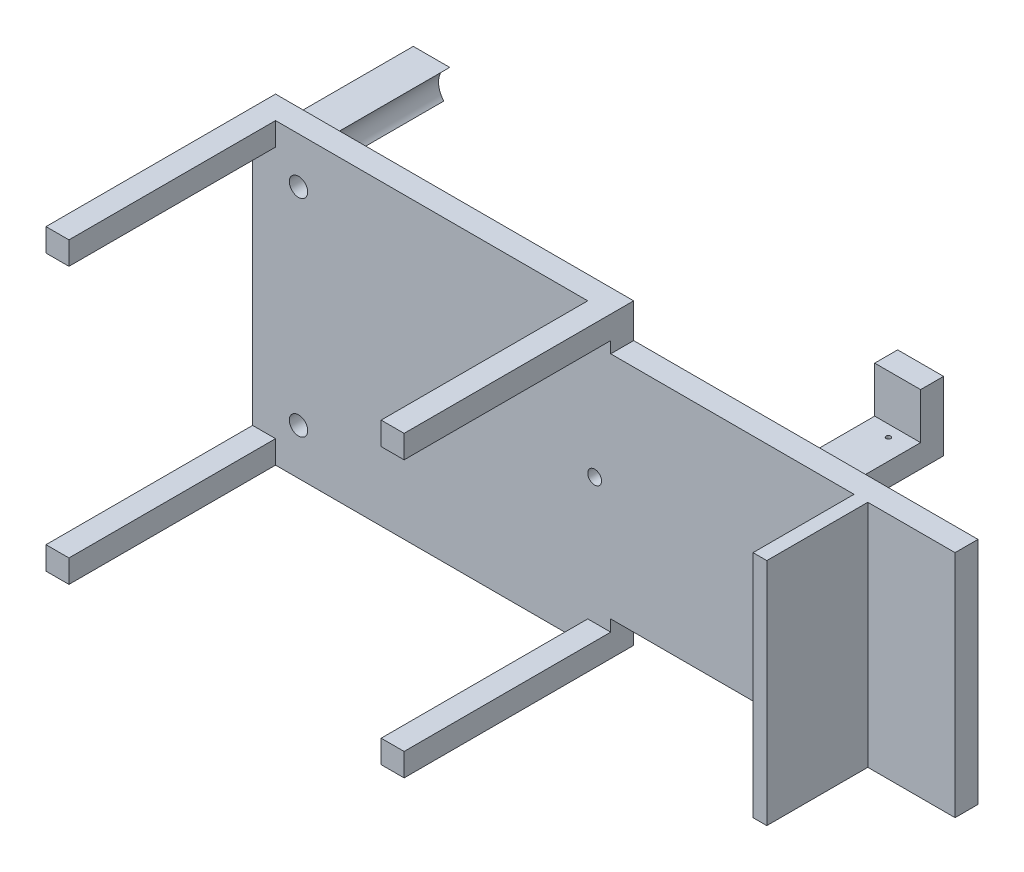
SolidWorks part; units mm, degrees
ref_plane "Alzado" through (0, 0, 0) normal (0, 0, 1) x (1, 0, 0)
ref_plane "Planta" through (0, 0, 0) normal (0, 1, 0) x (1, 0, 0)
ref_plane "Vista lateral" through (0, 0, 0) normal (1, 0, 0) x (0, 0, -1)
sketch "Croquis1" plane through (0, 0, 0) normal (0, 0, 1) x (1, 0, 0)
  line L1 (-76.5, -32.5) -> (1.5, -32.5)
  line L2 (-76.5, -32.5) -> (-76.5, 32.5)
  line L3 (-76.5, 32.5) -> (1.5, 32.5)
  line L4 (76.5, -25) -> (76.5, 25)
  line L5 (-76.5, 0) -> (127.0996, 0) construction
  line L6 (1.5, 32.5) -> (-3.5, 32.5)
  line L7 (-76.5, 27.5) -> (1.5, 27.5) construction
  line L8 (-76.5, -27.5) -> (1.5, -27.5) construction
  line L9 (-71.5, 0) -> (-61.5, 0) construction
  line L10 (1.5, -32.5) -> (1.5, 32.5)
  line L11 (-76.5, -32.5) -> (-71.5, -32.5)
  line L12 (1.5, -32.5) -> (-3.5, -32.5)
  line L13 (1.5, -32.5) -> (1.5, -27.5)
  line L14 (1.5, -27.5) -> (-3.5, -27.5)
  line L15 (76.5, 25) -> (1.5, 25)
  line L16 (76.5, -25) -> (1.5, -25)
  line L17 (-3.5, -32.5) -> (-3.5, -27.5)
  line L18 (-76.5, -32.5) -> (-76.5, -27.5)
  line L19 (-76.5, -27.5) -> (-71.5, -27.5)
  line L20 (-71.5, -32.5) -> (-71.5, -27.5)
  line L21 (-76.5, 32.5) -> (-71.5, 32.5)
  line L22 (-76.5, 32.5) -> (-76.5, 27.5)
  line L23 (-76.5, 27.5) -> (-71.5, 27.5)
  line L24 (-71.5, 32.5) -> (-71.5, 27.5)
  line L25 (1.5, 32.5) -> (1.5, 27.5)
  line L26 (1.5, 27.5) -> (-3.5, 27.5)
  line L27 (-3.5, 32.5) -> (-3.5, 27.5)
  circle A0 centre (-66.5, 22.5) radius 2
  circle A1 centre (-66.5, -22.5) radius 2
  circle A2 centre (-2, 0) radius 1.5
  point P0 (0, 0)
  point P12 (-41.5, 0)
  dimension "D5" = 78
  dimension "D10" = 4
  dimension "D11" = 4
  dimension "D12" = 5
  dimension "D13" = 65
  dimension "D15" = 3
  dimension "D16" = 3.5
  dimension "D1" = 45
  dimension "D2" = 5
  dimension "D3" = 5
  dimension "D4" = 55
  dimension "D6" = 50
  dimension "D7" = 5
  dimension "D8" = 10
  dimension "D9" = 10
  dimension "D14" = 5
  dimension "D17" = 50
  dimension "D18" = 75
  dimension "D19" = 153
  dimension "D20" = 7.5
  dimension "D21" = 5
  dimension "D22" = 78.5
extrude "Saliente-Extruir4" add sketch "Croquis1" along normal blind 5 contours L27 L3 L24 L23 L2 L19 L20 L1 L17 L14 L10 L26 A2 A0 A1 | L16 L4 L15 L10
sketch "Croquis3" plane through (0, 0, 0) normal (0, 0, -1) x (-1, 0, 0)
  line L0 (82.1817, 0) -> (-113.6683, 0) construction
  line L1 (-1.5, -27.5) -> (-1.5, -38.9029) construction
  line L2 (3.5, -32.5) -> (-4.0681, -32.5) construction
  line L3 (76.5, 32.5) -> (71.5, 32.5)
  line L4 (76.5, 32.5) -> (76.5, 27.5)
  line L5 (76.5, 27.5) -> (71.5, 27.5)
  line L6 (71.5, 32.5) -> (71.5, 27.5)
  line L7 (3.5, -32.5) -> (3.5, -27.5)
  line L8 (-1.5, -27.5) -> (3.5, -27.5)
  line L9 (3.5, 32.5) -> (-4.0681, 32.5) construction
  line L10 (-1.5, 27.5) -> (-1.5, 38.9029) construction
  line L11 (-1.5, -32.5) -> (-1.5, -27.5)
  line L12 (-1.5, 32.5) -> (3.5, 32.5)
  line L13 (-1.5, 32.5) -> (-1.5, 27.5)
  line L14 (-1.5, 27.5) -> (3.5, 27.5)
  line L15 (3.5, 32.5) -> (3.5, 27.5)
  line L16 (-1.5, -32.5) -> (3.5, -32.5)
  line L17 (71.5, -32.5) -> (71.5, -27.5)
  line L18 (76.5, -27.5) -> (71.5, -27.5)
  line L19 (76.5, -32.5) -> (76.5, -27.5)
  line L20 (76.5, -32.5) -> (71.5, -32.5)
extrude "Saliente-Extruir5" add sketch "Croquis3" against normal blind 50
sketch "Croquis4" plane through (0, 0, 5) normal (0, 0, 1) x (1, 0, 0)
  line L0 (76.5, -25) -> (76.5, 25) construction
  line L4 (76.5, -25) -> (1.5, -25) construction
  line L6 (57.5, 25) -> (54.5, 25)
  line L7 (57.5, 25) -> (57.5, -25)
  line L9 (57.5, -25) -> (54.5, -25)
  line L10 (54.5, 25) -> (54.5, -25)
  dimension "D1" = 3
  dimension "D2" = 50
  dimension "D3" = 19
extrude "Saliente-Extruir7" add sketch "Croquis4" along normal blind 22
sketch "Croquis6" plane through (0, 0, 0) normal (0, 0, -1) x (-1, 0, 0)
  line L0 (-1.5, 25) -> (-1.5, -25) construction
  line L1 (-1.5, 0) -> (-31.5, 0) construction
  line L2 (-31.5, 25) -> (-31.5, -25)
  line L3 (-76.5, 25) -> (-1.5, 25) construction
  line L4 (-76.5, -25) -> (-1.5, -25) construction
  line L5 (-41.5, 25) -> (-41.5, -25)
  line L6 (-76.5, 0) -> (10.0183, 0) construction
  line L7 (-76.5, -25) -> (-76.5, 25) construction
  line L8 (-41.5, -14.5) -> (-31.5, -14.5)
  line L9 (-41.5, 9.5) -> (-31.5, 9.5) construction
  line L10 (-41.5, -9.5) -> (-31.5, -9.5) construction
  line L11 (-41.5, 14.5) -> (-31.5, 14.5)
  line L12 (-41.5, 13.5) -> (-41.5, 9.5)
  line L13 (-31.5, 13.5) -> (-31.5, 9.5)
  line L14 (-31.5, -9.5) -> (-31.5, -13.5)
  line L15 (-41.5, -9.5) -> (-41.5, -13.5)
  line L17 (-41.5, 9.5) -> (-31.5, 9.5)
  line L18 (-41.5, 9.5) -> (-41.5, 13.5)
  line L20 (-31.5, 9.5) -> (-31.5, 13.5)
  line L22 (-41.5, -13.5) -> (-41.5, -9.5)
  line L23 (-41.5, -9.5) -> (-31.5, -9.5)
  line L24 (-31.5, -13.5) -> (-31.5, -9.5)
  point P24 (-51.481, 0)
  dimension "D1" = 10
  dimension "D2" = 30
  dimension "D3" = 5
  dimension "D4" = 10
  dimension "D5" = 19
  dimension "D6" = 5
extrude "Saliente-Extruir9" add sketch "Croquis6" along normal blind 27.5 contours L5 L17 L2 L11 | L23 L5 L8 L2
sketch "Croquis7" plane through (0, 14.5, 0) normal (0, 1, 0) x (1, 0, 0)
  line L0 (41.5, 27.5) -> (41.5, 0) construction
  line L1 (31.5, 27.5) -> (41.5, 27.5)
  line L2 (31.5, 27.5) -> (31.5, 22.5)
  line L3 (31.5, 22.5) -> (41.5, 22.5)
  line L4 (41.5, 27.5) -> (41.5, 22.5)
  dimension "D1" = 5
extrude "Saliente-Extruir10" add sketch "Croquis7" along normal blind 10
sketch "Croquis8" plane through (0, -14.5, 0) normal (0, -1, 0) x (1, 0, 0)
  line L0 (31.5, -27.5) -> (31.5, 0) construction
  line L1 (41.5, -27.5) -> (31.5, -27.5)
  line L2 (41.5, -27.5) -> (41.5, -22.5)
  line L3 (41.5, -22.5) -> (31.5, -22.5)
  line L4 (31.5, -27.5) -> (31.5, -22.5)
  dimension "D1" = 5
extrude "Saliente-Extruir11" add sketch "Croquis8" along normal blind 10
sketch "Croquis9" plane through (0, 0, 0) normal (0, 0, -1) x (-1, 0, 0)
  line L0 (-1.5, 0) -> (60.5, 0) construction
  line L1 (60.5, 32.5) -> (60.5, -32.5) construction
  line L2 (76.5, 32.5) -> (-1.5, 32.5) construction
  line L3 (76.5, -32.5) -> (-1.5, -32.5) construction
  line L4 (74.1097, 26.5) -> (74.1097, 19.5) construction
  line L5 (68.5, 22.5) -> (71, 22.5) construction
  line L6 (76.5, 26.5) -> (68.5616, 26.5) construction
  line L7 (69.8541, -19.5) -> (76.5, -19.5)
  line L8 (76.5, -32.5) -> (76.5, 32.5) construction
  line L9 (76.5, 19.5) -> (69.8541, 19.5) construction
  line L11 (76.5, -19.5) -> (69.8541, -19.5) construction
  line L12 (76.5, -26.5) -> (68.5616, -26.5) construction
  line L13 (68.5616, -26.5) -> (76.5, -26.5)
  line L14 (76.5, -26.5) -> (76.5, -19.5)
  line L15 (68.5616, 26.5) -> (76.5, 26.5)
  line L16 (76.5, 26.5) -> (76.5, 19.5)
  line L17 (76.5, 19.5) -> (69.8541, 19.5)
  circle A0 centre (66.5, 22.5) radius 2 construction
  arc A1 (69.8541, 19.5) -> (68.5616, 26.5) centre (66.5, 22.5) ccw
  arc A2 (69.8541, -19.5) -> (68.5616, -26.5) centre (66.5, -22.5) cw
extrude "Saliente-Extruir12" add sketch "Croquis9" along normal blind 30
sketch "Croquis10" plane through (0, -14.5, 0) normal (0, -1, 0) x (1, 0, 0)
  line L0 (35.5, -22.5) -> (35.5, 0) construction
  line L1 (41.5, -22.5) -> (31.5, -22.5) construction
  line L2 (76.5, 0) -> (1.5, 0) construction
  line L3 (31.5, -22.5) -> (31.5, 0) construction
  line L4 (31.5, -1) -> (41.5, -1) construction
  line L5 (41.5, -22.5) -> (41.5, 0) construction
  line L6 (37, -19.5) -> (37, -5.5) construction
  line L7 (41.5, -22.5) -> (31.5, -22.5) construction
  line L8 (41.5, -21.5) -> (31.5, -21.5) construction
  line L9 (37, -5.5) -> (37, -4) construction
  circle A1 centre (37, -4) radius 0.5
  circle A2 centre (37, -20) radius 0.5
  dimension "D3" = 1
  dimension "D5" = 4
  dimension "D7" = 2.5
  dimension "D9" = 1
  dimension "D1" = 4
  dimension "D2" = 1
  dimension "D4" = 4.5
  dimension "D6" = 1
  dimension "D8" = 5.5
extrude "Cortar-Extruir2" cut sketch "Croquis10" against normal blind 43
